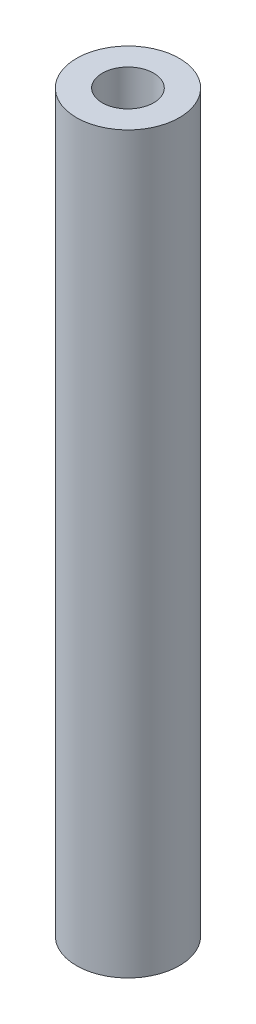
SolidWorks part; units mm, degrees
material "6061 Alloy"
ref_plane "Front Plane" through (0, 0, 0) normal (0, 0, 1) x (1, 0, 0)
ref_plane "Top Plane" through (0, 0, 0) normal (0, 1, 0) x (1, 0, 0)
ref_plane "Right Plane" through (0, 0, 0) normal (1, 0, 0) x (0, 0, -1)
sketch "Sketch1" plane through (0, 0, 0) normal (0, 1, 0) x (1, 0, 0)
  circle A0 centre (0, 0) radius 1.75
  circle A1 centre (0, 0) radius 3.5
  dimension "D1" = 3.5
  dimension "D2" = 7
extrude "Boss-Extrude1" add sketch "Sketch1" along normal blind 50
